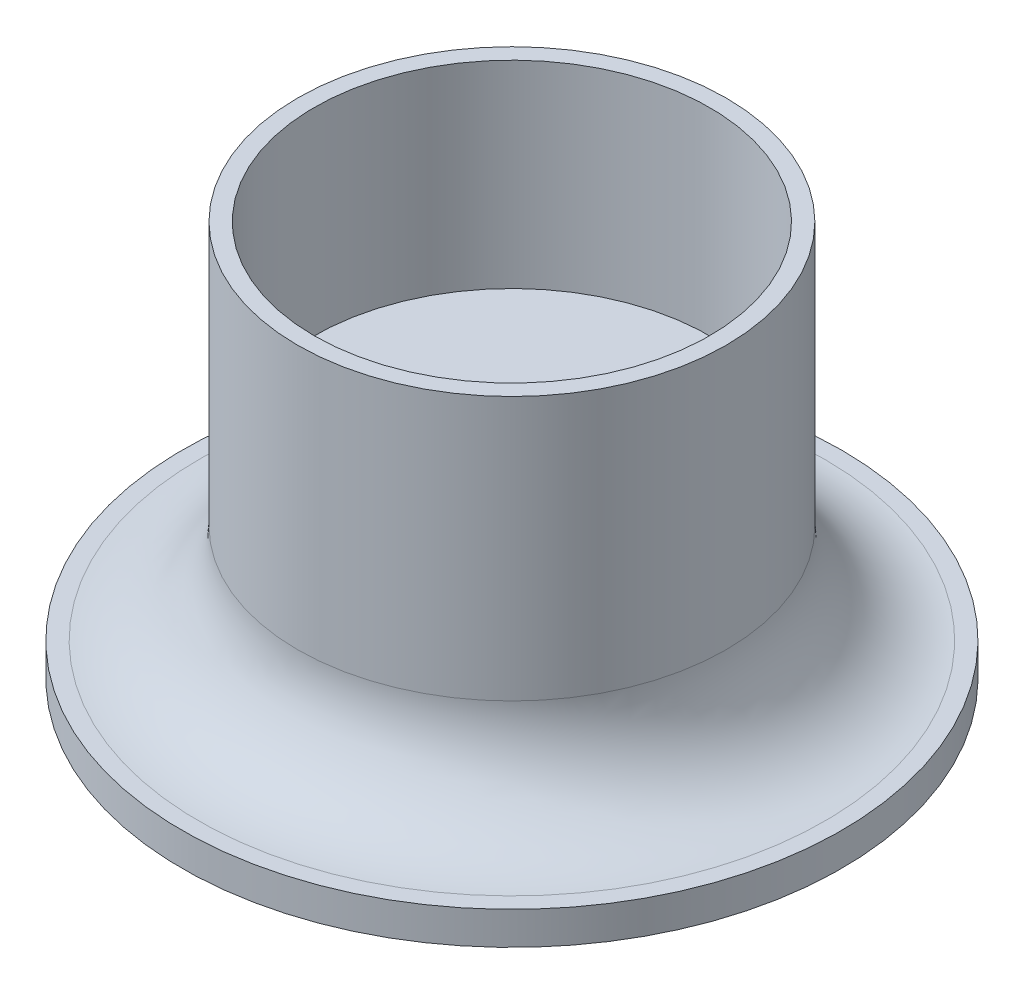
SolidWorks part; units mm, degrees
ref_plane "前视基准面" through (0, 0, 0) normal (0, 0, 1) x (1, 0, 0)
ref_plane "上视基准面" through (0, 0, 0) normal (0, 1, 0) x (1, 0, 0)
ref_plane "右视基准面" through (0, 0, 0) normal (1, 0, 0) x (0, 0, -1)
sketch "草图1" plane through (0, 0, 0) normal (0, 1, 0) x (1, 0, 0)
  circle A0 centre (0, 0) radius 65
  dimension "D1" = 130
extrude "凸台-拉伸1" add sketch "草图1" along normal blind 50
sketch "草图2" plane through (0, 50, 0) normal (0, 1, 0) x (1, 0, 0)
  circle A0 centre (0, 0) radius 60
  circle A1 centre (0, 0) radius 65
  circle A2 centre (0, 0) radius 65
  dimension "D2" = 120
  dimension "D1" = 0
extrude "凸台-拉伸2" add sketch "草图2" along normal blind 60
sketch "草图3" plane through (0, 0, 0) normal (0, -1, 0) x (1, 0, 0)
  circle A0 centre (0, 0) radius 100
  dimension "D1" = 200
extrude "凸台-拉伸3" add sketch "草图3" along normal blind 10
fillet "圆角1" radius 30 1 edges at (0, 0, 65)
